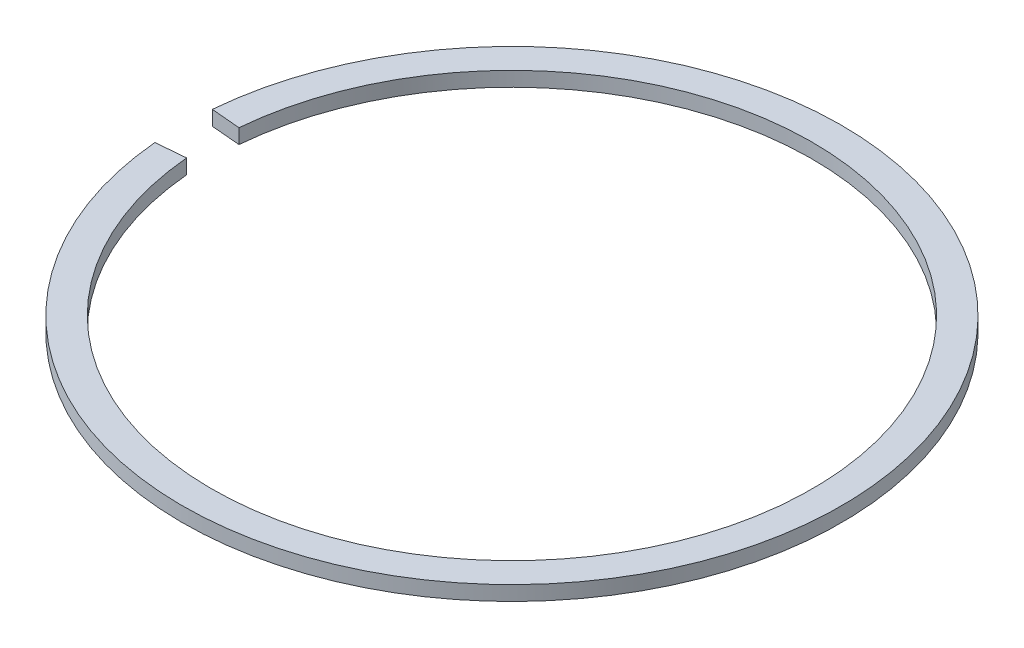
SolidWorks part; units mm, degrees
material "Teak"
ref_plane "Plano frontal" through (0, 0, 0) normal (0, 0, 1) x (1, 0, 0)
ref_plane "Plano superior" through (0, 0, 0) normal (0, 1, 0) x (1, 0, 0)
ref_plane "Plano direito" through (0, 0, 0) normal (1, 0, 0) x (0, 0, -1)
sketch "Sketch1" plane through (0, 0, 0) normal (0, 0, 1) x (1, 0, 0)
  line L0 (0, 0) -> (0, 8.2887) construction
  line L2 (41, 2) -> (45, 2)
  line L3 (41, 2) -> (41, 0)
  line L4 (41, 0) -> (45, 0)
  line L5 (45, 2) -> (45, 0)
  dimension "D1" = 4
  dimension "D2" = 41
  dimension "D3" = 2
revolve "Revolve1" add sketch "Sketch1" angle 350 mid plane about L0
